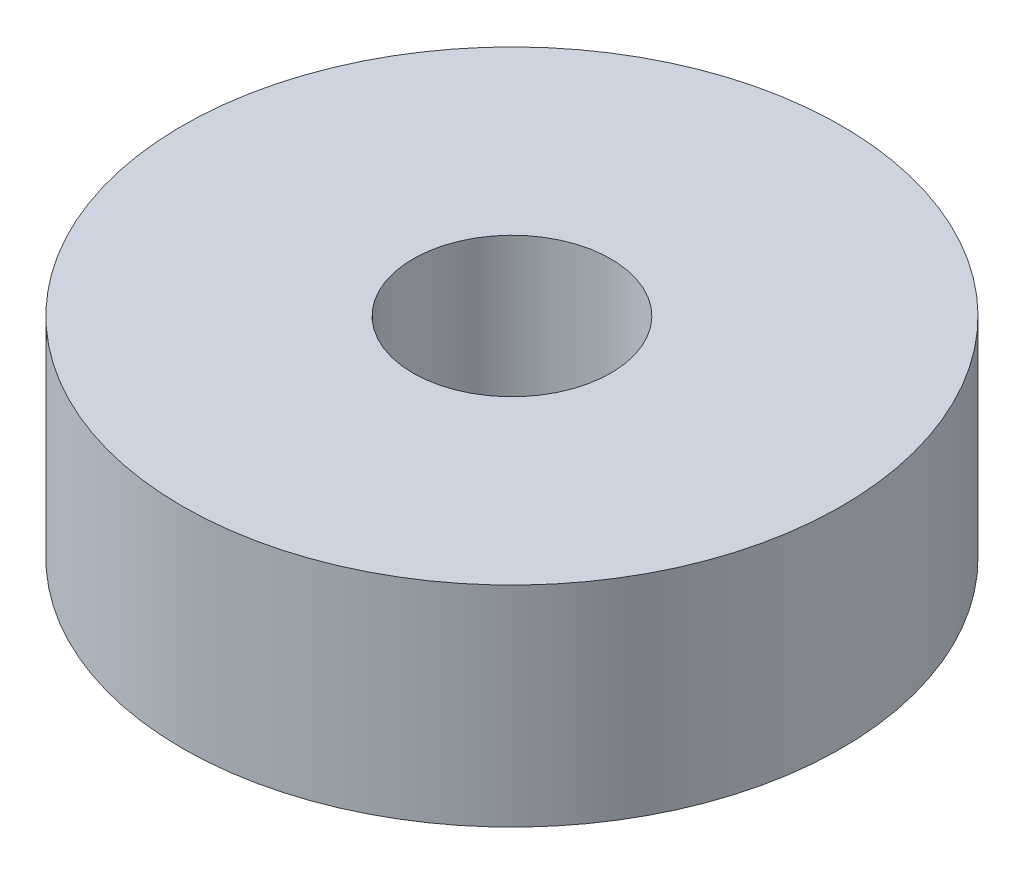
SolidWorks part; units mm, degrees
material "Acrylic (Medium-high impact)"
ref_plane "Front Plane" through (0, 0, 0) normal (0, 0, 1) x (1, 0, 0)
ref_plane "Top Plane" through (0, 0, 0) normal (0, 1, 0) x (1, 0, 0)
ref_plane "Right Plane" through (0, 0, 0) normal (1, 0, 0) x (0, 0, -1)
sketch "Sketch1" plane through (0, 0, 0) normal (0, 1, 0) x (1, 0, 0)
  line L0 (-3.3074, 0.9678) -> (6.6748, 0.9678) construction
  circle A0 centre (1.6837, 0.9678) radius 4.9911
  circle A1 centre (1.6837, 0.9678) radius 1.4986
  dimension "D1" = 2.9972
  dimension "D3" = 9.9822
extrude "Boss-Extrude1" add sketch "Sketch1" along normal blind 3.175
